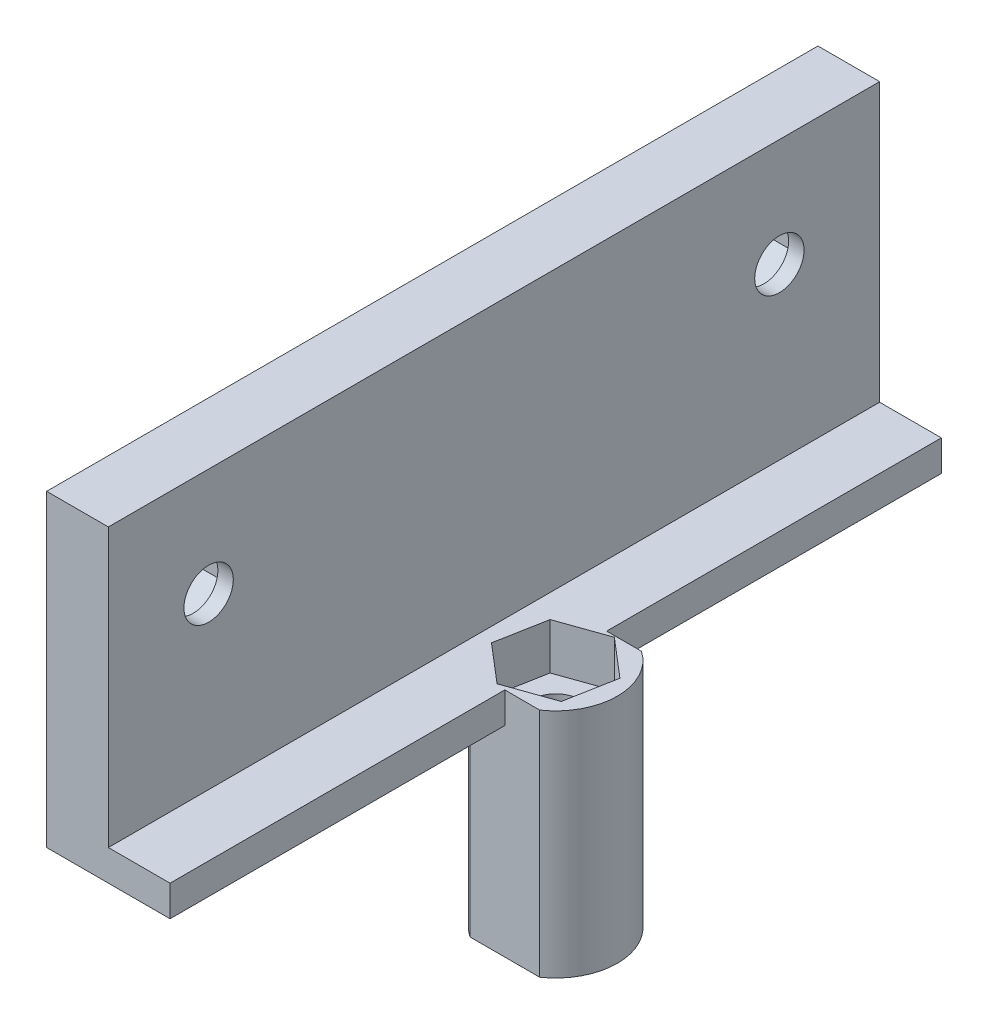
SolidWorks part; units mm, degrees
ref_plane "Alzado" through (0, 0, 0) normal (0, 0, 1) x (1, 0, 0)
ref_plane "Planta" through (0, 0, 0) normal (0, 1, 0) x (1, 0, 0)
ref_plane "Vista lateral" through (0, 0, 0) normal (1, 0, 0) x (0, 0, -1)
sketch "Croquis5" plane through (0, 0, 0) normal (0, 1, 0) x (1, 0, 0)
  line L0 (-65.6098, 16.7628) -> (-61.0888, 16.7628)
  line L1 (-63.3493, 13.4628) -> (-59.3493, 13.4628) construction
  line L2 (-59.3493, 13.4628) -> (-67.3493, 13.4628) construction
  line L3 (-65.6098, 10.1628) -> (-61.0888, 10.1628)
  circle A0 centre (-63.3493, 13.4628) radius 1.6
  arc A1 (-65.6098, 16.7628) -> (-65.6098, 10.1628) centre (-63.3493, 13.4628) ccw
  arc A2 (-61.0888, 10.1628) -> (-61.0888, 16.7628) centre (-63.3493, 13.4628) ccw
  dimension "D1" = 3.2
  dimension "D2" = 8
  dimension "D3" = 3.3
extrude "Saliente-Extruir3" add sketch "Croquis5" along normal blind 15
sketch "Croquis7" plane through (0, 15, 0) normal (0, 1, 0) x (1, 0, 0)
  line L0 (-63.3493, 13.4628) -> (-63.3493, -11.5372)
  line L1 (-63.3493, -11.5372) -> (-71.3493, -11.5372)
  line L2 (-71.3493, -11.5372) -> (-71.3493, 38.4628)
  line L3 (-71.3493, 38.4628) -> (-63.3493, 38.4628)
  line L4 (-63.3493, 38.4628) -> (-63.3493, 13.4628)
  dimension "D1" = 50
  dimension "D2" = 25
  dimension "D3" = 8
extrude "Saliente-Extruir5" add sketch "Croquis7" against normal blind 2
sketch "Croquis9" plane through (0, 15, 0) normal (0, 1, 0) x (1, 0, 0)
  line L1 (-60.2742, 14.5513) -> (-62.7544, 16.6701)
  line L2 (-62.7544, 16.6701) -> (-65.8295, 15.5816)
  line L3 (-65.8295, 15.5816) -> (-66.4243, 12.3743)
  line L4 (-66.4243, 12.3743) -> (-63.9441, 10.2555)
  line L5 (-63.9441, 10.2555) -> (-60.8691, 11.344)
  line L6 (-60.8691, 11.344) -> (-60.2742, 14.5513)
  circle A0 centre (-63.3493, 13.4628) radius 2.825 construction
  point P1 (0, 0)
  dimension "D1" = 5.65
extrude "Cortar-Extruir3" cut sketch "Croquis9" against normal blind 3
sketch "Croquis10" plane through (0, 15, 0) normal (0, 1, 0) x (1, 0, 0)
  line L0 (-71.3493, 38.4628) -> (-67.3493, 38.4628)
  line L1 (-63.3493, 38.4628) -> (-71.3493, 38.4628) construction
  line L2 (-67.3493, 38.4628) -> (-67.3493, -11.5372)
  line L3 (-71.3493, -11.5372) -> (-63.3493, -11.5372) construction
  line L4 (-67.3493, -11.5372) -> (-71.3493, -11.5372)
  line L5 (-71.3493, -11.5372) -> (-71.3493, 38.4628)
extrude "Saliente-Extruir6" add sketch "Croquis10" along normal blind 18
sketch "Croquis17" plane through (-67.3493, 0, 0) normal (1, 0, 0) x (0, 0, -1)
  line L0 (-11.5372, 33) -> (-11.5372, 15) construction
  line L2 (13.4628, 15) -> (13.4628, 41.5406) construction
  line L3 (-11.5372, 15) -> (38.4628, 15) construction
  line L4 (-11.5372, 33) -> (38.4628, 33) construction
  circle A0 centre (-5.0372, 26) radius 1.6
  circle A1 centre (31.9628, 26) radius 1.6
  dimension "D1" = 6.5
  dimension "D3" = 3.2
  dimension "D2" = 7
extrude "Cortar-Extruir4" cut sketch "Croquis17" against normal blind 4
sketch "Croquis19" plane through (-71.3493, 0, 0) normal (-1, 0, 0) x (0, 0, 1)
  line L0 (-13.4628, 13) -> (-13.4628, 37.9075) construction
  line L1 (-31.9628, 29.2332) -> (-34.7628, 27.6166)
  line L2 (-34.7628, 27.6166) -> (-34.7628, 24.3834)
  line L3 (-34.7628, 24.3834) -> (-31.9628, 22.7668)
  line L4 (-31.9628, 22.7668) -> (-29.1628, 24.3834)
  line L5 (-29.1628, 24.3834) -> (-29.1628, 27.6166)
  line L6 (-29.1628, 27.6166) -> (-31.9628, 29.2332)
  line L13 (-38.4628, 13) -> (11.5372, 13) construction
  line L14 (2.2372, 27.6166) -> (5.0372, 29.2332)
  line L15 (2.2372, 24.3834) -> (2.2372, 27.6166)
  line L16 (5.0372, 22.7668) -> (2.2372, 24.3834)
  line L17 (7.8372, 24.3834) -> (5.0372, 22.7668)
  line L18 (7.8372, 27.6166) -> (7.8372, 24.3834)
  line L19 (5.0372, 29.2332) -> (7.8372, 27.6166)
  circle A0 centre (-31.9628, 26) radius 2.8 construction
  point P1 (0, 0)
  dimension "D1" = 5.6
extrude "Cortar-Extruir6" cut sketch "Croquis19" against normal blind 3
